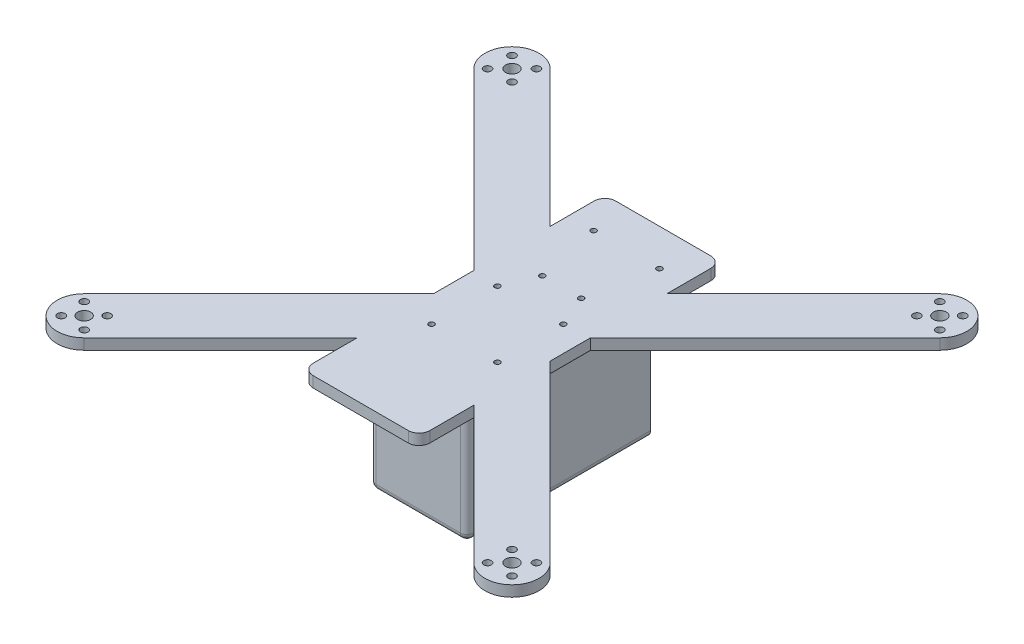
SolidWorks part; units mm, degrees
material "PE High Density"
ref_plane "Front Plane" through (0, 0, 0) normal (0, 0, 1) x (1, 0, 0)
ref_plane "Top Plane" through (0, 0, 0) normal (0, 1, 0) x (1, 0, 0)
ref_plane "Right Plane" through (0, 0, 0) normal (1, 0, 0) x (0, 0, -1)
sketch "Sketch2" plane through (0, 0, 0) normal (0, 1, 0) x (1, 0, 0)
  line L0 (0, 0) -> (0, -70) construction
  line L1 (-27, 70) -> (27, 70)
  line L2 (-27, 70) -> (-27, 44.6777)
  line L3 (-27, -70) -> (27, -70)
  line L4 (27, 70) -> (27, 44.6777)
  line L5 (-27, 70) -> (27, -70) construction
  line L6 (-27, -70) -> (27, 70) construction
  line L7 (0, 0) -> (-98.9949, -98.9949) construction
  line L8 (-107.8338, -90.1561) -> (-27, -9.3223)
  line L9 (-90.1561, -107.8338) -> (-27, -44.6777)
  line L10 (107.8338, -90.1561) -> (27, -9.3223)
  line L11 (90.1561, -107.8338) -> (27, -44.6777)
  line L12 (0, 0) -> (98.9949, -98.9949) construction
  line L13 (0, 0) -> (27, 0) construction
  line L14 (107.8338, 90.1561) -> (27, 9.3223)
  line L15 (0, 0) -> (98.9949, 98.9949) construction
  line L16 (90.1561, 107.8338) -> (27, 44.6777)
  line L17 (-90.1561, 107.8338) -> (-27, 44.6777)
  line L18 (0, 0) -> (-98.9949, 98.9949) construction
  line L19 (-107.8338, 90.1561) -> (-27, 9.3223)
  line L20 (-27, -44.6777) -> (-27, -70)
  line L21 (27, -44.6777) -> (27, -70)
  line L22 (27, 9.3223) -> (27, -9.3223)
  line L23 (-27, 9.3223) -> (-27, -9.3223)
  arc A0 (-107.8338, -90.1561) -> (-90.1561, -107.8338) centre (-98.9949, -98.9949) ccw
  arc A1 (107.8338, -90.1561) -> (90.1561, -107.8338) centre (98.9949, -98.9949) cw
  arc A2 (107.8338, 90.1561) -> (90.1561, 107.8338) centre (98.9949, 98.9949) ccw
  arc A3 (-107.8338, 90.1561) -> (-90.1561, 107.8338) centre (-98.9949, 98.9949) cw
  point P0 (0, 0)
  dimension "D5" = 25
  dimension "D1" = 54
  dimension "D2" = 140
  dimension "D3" = 45
  dimension "D4" = 140
extrude "Boss-Extrude1" add sketch "Sketch2" along normal blind 5
sketch "Sketch3" plane through (0, 5, 0) normal (0, 1, 0) x (1, 0, 0)
  line L0 (-98.9949, -98.9949) -> (-107.8338, -107.8338) construction
  line L1 (-98.9949, -98.9949) -> (-90.1561, -107.8338) construction
  circle A0 centre (-98.9949, -98.9949) radius 3
  arc A1 (-107.8338, -90.1561) -> (-90.1561, -107.8338) centre (-98.9949, -98.9949) ccw construction
  circle A2 centre (-104.2983, -104.2983) radius 1.75
  circle A3 centre (-93.3381, -104.6518) radius 1.75
  circle A4 centre (-104.6518, -93.3381) radius 1.75
  circle A5 centre (-93.6916, -93.6916) radius 1.75
  point P20 (-95.314, -95.314)
  dimension "D1" = 6
  dimension "D2" = 3.5
  dimension "D3" = 15
  dimension "D4" = 16
extrude "Cut-Extrude1" cut sketch "Sketch3" against normal up to next
mirror "Mirror1" about plane through (0, 0, 0) normal (1, 0, 0) of "Cut-Extrude1"
mirror "Mirror2" about plane through (0, 0, 0) normal (0, 0, 1) of "Cut-Extrude1", "Mirror1"
hole_wizard "M3x0.5 Tapped Hole1" positions "Sketch4" profile "Sketch5" tap size "M3x0.5" standard "JIS" end condition up to next
sketch "Sketch4" plane through (0, 5, 0) normal (0, 1, 0) x (1, 0, 0)
  line L0 (-27, -70) -> (27, -70) construction
  line L1 (0, 70) -> (0, -70) construction
  line L2 (27, 70) -> (-27, 70) construction
  point P0 (-15.25, -22)
  point P2 (15.25, -22)
  point P4 (-15.25, 8.5)
  point P6 (15.25, 8.5)
  point P8 (-9, 23)
  point P10 (9, 23)
  point P12 (-15.25, 53)
  point P14 (15.25, 53)
  dimension "D1" = 48
  dimension "D2" = 30.5
  dimension "D3" = 30.5
  dimension "D4" = 93
  dimension "D5" = 30
  dimension "D6" = 18
  dimension "D7" = 30.5
sketch "Sketch5" plane through (-15.25, 5, 22) normal (1, 0, 0) x (0, 0, 1)
  line L0 (0, 0) -> (0, 5)
  line L1 (0, 5) -> (1.25, 5)
  line L2 (1.25, 5) -> (1.25, 0)
  line L5 (1.25, 0) -> (0, 0)
  line L11 (0, -6.35) -> (0, 107.95) construction
  dimension "Thru Tap Drill Dia." = 2.5
  dimension "Thru Tap Drill Depth" = 5
cosmetic thread "Hole Thread1" parameters "D2"=3
cosmetic thread "Hole Thread2" parameters "D2"=3
cosmetic thread "Hole Thread3" parameters "D2"=3
cosmetic thread "Hole Thread4" parameters "D2"=3
cosmetic thread "Hole Thread5" parameters "D2"=3
cosmetic thread "Hole Thread6" parameters "D2"=3
cosmetic thread "Hole Thread7" parameters "D2"=3
cosmetic thread "Hole Thread8" parameters "D2"=3
sketch "Sketch6" plane through (0, 0, 0) normal (0, -1, 0) x (1, 0, 0)
  line L0 (-15.881, -40) -> (-20.881, -40)
  line L1 (-20.881, -40) -> (-20.881, 45)
  line L2 (-20.881, 45) -> (24.119, 45)
  line L3 (24.119, 45) -> (24.119, -40)
  line L4 (24.119, -40) -> (19.119, -40)
  line L5 (19.119, -40) -> (19.119, 40)
  line L6 (19.119, 40) -> (-15.881, 40)
  line L7 (-15.881, 40) -> (-15.881, -40)
  line L8 (0, 0) -> (0, 40) construction
  line L9 (0, 0) -> (-15.881, 0) construction
  dimension "D1" = 35
  dimension "D2" = 80
  dimension "D3" = 5
  dimension "D4" = 5
  dimension "D5" = 5
extrude "Boss-Extrude2" add sketch "Sketch6" along normal blind 47
sketch "Sketch7" plane through (0, -47, 0) normal (0, -1, 0) x (1, 0, 0)
  line L1 (-20.881, 45) -> (24.119, 45)
  line L2 (-20.881, 45) -> (-20.881, -40)
  line L3 (-20.881, -40) -> (24.119, -40)
  line L4 (24.119, 45) -> (24.119, -40)
extrude "Boss-Extrude3" add sketch "Sketch7" along normal blind 5
fillet "Fillet1" radius 5 4 edges at (-27, 2.5, -70) (27, 2.5, -70) (-27, 2.5, 70) (27, 2.5, 70)
fillet "Fillet2" radius 3 8 edges at (24.119, -52, 2.5) (1.619, -52, 45) (-20.881, -52, 2.5) (24.119, -26, 45) (-20.881, -26, 45) (-20.881, 0, 2.5) (1.619, 0, 45) (24.119, 0, 2.5)
